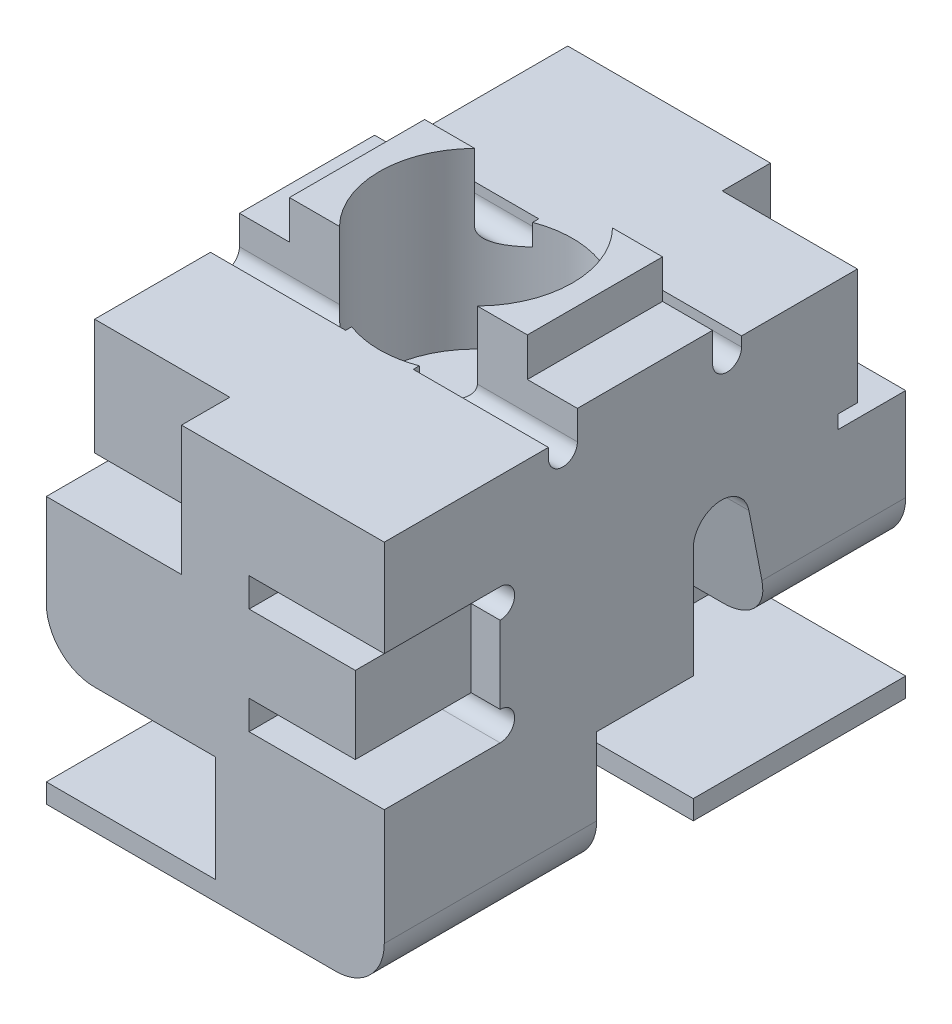
SolidWorks part; units mm, degrees
material "Brass"
ref_plane "Front Plane" through (0, 0, 0) normal (0, 0, 1) x (1, 0, 0)
ref_plane "Top Plane" through (0, 0, 0) normal (0, 1, 0) x (1, 0, 0)
ref_plane "Right Plane" through (0, 0, 0) normal (1, 0, 0) x (0, 0, -1)
sketch "Sketch1" plane through (0, 0, 0) normal (0, 1, 0) x (1, 0, 0)
  line L1 (0, 0) -> (4.445, 0)
  line L2 (0, 0) -> (0, 6.858)
  line L3 (0, 6.858) -> (4.445, 6.858)
  line L4 (4.445, 0) -> (4.445, 6.858)
  dimension "D1" = 4.445
  dimension "D2" = 6.858
extrude "Boss-Extrude1" add sketch "Sketch1" along normal blind 5.461
sketch "Sketch2" plane through (0, 5.461, 0) normal (0, 1, 0) x (1, 0, 0)
  line L0 (2.2225, 0) -> (2.2225, 6.858) construction
  line L1 (0, 0) -> (4.445, 0) construction
  line L2 (4.445, 6.858) -> (0, 6.858) construction
  circle A0 centre (2.2225, 3.429) radius 1.27
  dimension "D1" = 2.54
extrude "Cut-Extrude1" cut sketch "Sketch2" against normal blind 1.778
sketch "Sketch3" plane through (0, 0, 0) normal (-1, 0, 0) x (0, 0, 1)
  line L0 (-4.064, -1.651) -> (-4.064, 1.651)
  line L1 (-4.064, -1.651) -> (-2.794, -1.651)
  line L2 (-4.064, 1.651) -> (-2.794, 1.651)
  line L3 (-2.794, -1.651) -> (-2.794, 1.651)
  line L4 (-4.064, -1.651) -> (-2.794, 1.651) construction
  line L5 (-4.064, 1.651) -> (-2.794, -1.651) construction
  line L6 (-6.858, 0) -> (0, 0) construction
  point P1 (-3.429, 0)
  dimension "D1" = 1.27
  dimension "D2" = 3.302
extrude "Cut-Extrude2" cut sketch "Sketch3" against normal through all
sketch "Sketch4" plane through (0, 0, 0) normal (-1, 0, 0) x (0, 0, 1)
  line L0 (-2.794, 1.651) -> (-2.794, 3.1131)
  line L1 (-2.0619, 3.1692) -> (-1.7677, 1.651)
  line L2 (-1.7677, 1.651) -> (0, 1.651)
  line L3 (0, 5.461) -> (0, 0) construction
  line L4 (-2.794, 1.651) -> (-2.794, 0.254)
  line L5 (-2.794, 0.254) -> (0, 0.254)
  line L6 (0, 0.254) -> (0, 1.651)
  line L7 (-2.794, 0) -> (0, 0) construction
  arc A0 (-2.0619, 3.1692) -> (-2.794, 3.1131) centre (-2.4247, 3.0989) ccw
  dimension "D1" = 0.254
extrude "Cut-Extrude3" cut sketch "Sketch4" against normal offset from surface (2.2225 mm away) 2.2225 up to face at (4.445, 1.778, -3.429)
sketch "Sketch11" plane through (4.445, 0, 0) normal (1, 0, 0) x (0, 0, -1)
  line L2 (0, 1.651) -> (1.7677, 1.651) construction
  line L5 (2.794, 0.254) -> (2.794, 1.651) construction
  line L6 (6.858, 1.651) -> (6.858, 0.254)
  line L7 (4.064, 0.254) -> (6.858, 0.254)
  line L8 (4.064, 0) -> (6.858, 0) construction
  line L9 (0, 5.461) -> (0, -0.0004)
  line L10 (0, 5.461) -> (6.858, 5.461) construction
  line L12 (3.429, 5.461) -> (3.429, 1.651) construction
  line L13 (4.064, 0.254) -> (4.064, 1.651)
  line L15 (6.858, 1.651) -> (5.0903, 1.651)
  line L16 (5.0903, 1.651) -> (4.7961, 3.1692)
  line L17 (4.064, 3.1131) -> (4.064, 1.651)
  arc A0 (2.794, 3.1131) -> (2.0619, 3.1692) centre (2.4247, 3.0989) ccw construction
  arc A2 (4.064, 3.1131) -> (4.7961, 3.1692) centre (4.4333, 3.0989) cw
  line M9 (4.064, 1.651) -> (4.064, 0)
  line M11 (6.858, 0) -> (6.858, 5.461)
  dimension "D1" = 0.254
extrude "Cut-Extrude4" cut sketch "Sketch11" against normal up to surface (2.2225 mm away) contours A2 L17 L7 L15 L16 M9 M11 up to face at (2.2225, 1.7242, -1.7481)
sketch "Sketch12" plane through (4.445, 0, 0) normal (1, 0, 0) x (0, 0, -1)
  line L0 (0, 5.461) -> (0, 0) construction
  line L1 (0, 2.159) -> (1.524, 2.159)
  line L2 (0, 2.159) -> (0, 2.54)
  line L3 (0, 2.54) -> (1.524, 2.54)
  line L4 (2.794, 1.651) -> (4.064, 1.651) construction
  line L5 (0, 5.461) -> (6.858, 5.461) construction
  line L6 (0, 3.937) -> (1.524, 3.937)
  line L7 (0, 3.937) -> (0, 3.556)
  line L8 (0, 3.556) -> (1.524, 3.556)
  line L9 (2.54, 5.207) -> (2.54, 5.08)
  line L10 (0, 5.461) -> (2.54, 5.461)
  line L11 (0, 5.461) -> (0, 5.207)
  line L12 (0, 5.207) -> (2.159, 5.207)
  line L13 (2.54, 5.461) -> (2.54, 5.207)
  line L15 (4.699, 5.207) -> (4.318, 5.207) construction
  line L16 (4.699, 5.08) -> (4.699, 5.207)
  line L17 (6.858, 5.461) -> (6.858, 3.5052)
  line L18 (6.858, 5.461) -> (6.858, 1.651) construction
  line L19 (2.159, 5.08) -> (2.159, 5.207)
  line L20 (2.159, 5.207) -> (2.54, 5.207) construction
  line L21 (3.429, 5.461) -> (3.429, 1.651) construction
  line L22 (4.318, 5.461) -> (4.318, 5.207)
  line L23 (6.223, 5.207) -> (4.699, 5.207)
  line L25 (6.858, 5.461) -> (4.318, 5.461)
  line L26 (4.318, 5.207) -> (4.318, 5.08)
  line L27 (6.223, 5.207) -> (6.223, 3.683)
  line L28 (6.223, 3.683) -> (5.969, 3.683)
  line L29 (5.969, 3.683) -> (5.969, 3.5052)
  line L30 (5.969, 3.5052) -> (6.858, 3.5052)
  arc A0 (1.524, 3.937) -> (1.524, 3.556) centre (1.524, 3.7465) cw
  arc A1 (1.524, 2.54) -> (1.524, 2.159) centre (1.524, 2.3495) cw
  arc A2 (2.54, 5.08) -> (2.159, 5.08) centre (2.3495, 5.08) cw
  arc A3 (4.318, 5.08) -> (4.699, 5.08) centre (4.5085, 5.08) ccw
  dimension "D1" = 0.508
  dimension "D2" = 1.524
  dimension "D3" = 1.016
  dimension "D4" = 0.381
  dimension "D5" = 0.889
  dimension "D6" = 0.254
  dimension "D7" = 0.127
  dimension "D8" = 0.889
  dimension "D9" = 0.1778
  dimension "D10" = 0.635
  dimension "D11" = 1.524
extrude "Cut-Extrude6" cut sketch "Sketch12" against normal blind 1.778
sketch "Sketch13" plane through (0, 0, 0) normal (-1, 0, 0) x (0, 0, 1)
  line L0 (-6.858, 2.159) -> (-5.334, 2.159)
  line L1 (-6.858, 2.159) -> (-6.858, 2.54)
  line L2 (-6.858, 2.54) -> (-5.334, 2.54)
  line L3 (-6.858, 3.937) -> (-5.334, 3.937)
  line L4 (-6.858, 3.937) -> (-6.858, 3.556)
  line L5 (-6.858, 3.556) -> (-5.334, 3.556)
  line L6 (-4.318, 5.207) -> (-4.318, 5.08)
  line L7 (-6.858, 5.461) -> (-4.318, 5.461)
  line L8 (-6.858, 5.461) -> (-6.858, 5.207)
  line L9 (-6.858, 5.207) -> (-4.699, 5.207)
  line L10 (-4.318, 5.461) -> (-4.318, 5.207)
  line L11 (-2.159, 5.207) -> (-2.54, 5.207) construction
  line L12 (-2.159, 5.08) -> (-2.159, 5.207)
  line L13 (0, 5.461) -> (0, 3.5052)
  line L14 (-4.699, 5.08) -> (-4.699, 5.207)
  line L15 (-4.699, 5.207) -> (-4.318, 5.207) construction
  line L16 (-3.429, 5.461) -> (-3.429, 3.1024) construction
  line L17 (-2.54, 5.461) -> (-2.54, 5.207)
  line L18 (-0.635, 5.207) -> (-2.159, 5.207)
  line L19 (0, 5.461) -> (-2.54, 5.461)
  line L20 (-2.54, 5.207) -> (-2.54, 5.08)
  line L21 (-0.635, 5.207) -> (-0.635, 3.683)
  line L22 (-0.635, 3.683) -> (-0.889, 3.683)
  line L23 (-0.889, 3.683) -> (-0.889, 3.5052)
  line L24 (-0.889, 3.5052) -> (0, 3.5052)
  line L25 (-6.858, 5.461) -> (-6.858, 0) construction
  line L26 (-6.858, 5.461) -> (0, 5.461) construction
  arc A0 (-5.334, 3.937) -> (-5.334, 3.556) centre (-5.334, 3.7465) cw
  arc A1 (-5.334, 2.54) -> (-5.334, 2.159) centre (-5.334, 2.3495) cw
  arc A2 (-4.318, 5.08) -> (-4.699, 5.08) centre (-4.5085, 5.08) cw
  arc A3 (-2.54, 5.08) -> (-2.159, 5.08) centre (-2.3495, 5.08) ccw
  dimension "D1" = 1.524
  dimension "D2" = 1.016
  dimension "D3" = 0.381
  dimension "D4" = 0.889
  dimension "D5" = 0.254
  dimension "D6" = 0.127
  dimension "D7" = 0.889
  dimension "D8" = 0.1778
  dimension "D9" = 0.635
  dimension "D10" = 1.524
  dimension "D11" = 1.27
  dimension "D12" = 2.54
extrude "Cut-Extrude7" cut sketch "Sketch13" against normal blind 1.778
fillet "Fillet1" radius 0.635 4 edges at (4.445, 0, -1.397) (0, 0, -5.461) (4.445, 1.651, -5.9741) (0, 1.651, -0.8839)
sketch "Sketch14" plane through (0, 0, -6.858) normal (0, 0, -1) x (-1, 0, 0)
  line L1 (-2.667, 5.461) -> (-1.778, 5.461)
  line L2 (-2.667, 5.461) -> (-2.667, 5.207)
  line L3 (-2.667, 5.207) -> (-1.778, 5.207)
  line L4 (-1.778, 5.461) -> (-1.778, 5.207)
extrude "Cut-Extrude8" cut sketch "Sketch14" against normal through all
sketch "Sketch15" plane through (0, 5.461, 0) normal (0, 1, 0) x (1, 0, 0)
  line L0 (3.1295, 4.318) -> (3.7872, 4.318)
  line L1 (3.1295, 4.318) -> (4.445, 4.318) construction
  line L2 (3.7872, 4.318) -> (3.7872, 2.54)
  line L3 (3.1295, 2.54) -> (4.445, 2.54) construction
  line L4 (3.7872, 2.54) -> (3.1295, 2.54)
  line L5 (1.3155, 4.318) -> (0.6578, 4.318)
  line L6 (1.3155, 4.318) -> (0, 4.318) construction
  line L7 (0.6578, 4.318) -> (0.6578, 2.54)
  line L8 (1.3155, 2.54) -> (0, 2.54) construction
  line L9 (0.6578, 2.54) -> (1.3155, 2.54)
  arc A0 (1.3155, 4.318) -> (1.3155, 2.54) centre (2.2225, 3.429) ccw construction
  arc A1 (3.1295, 2.54) -> (3.1295, 4.318) centre (2.2225, 3.429) ccw construction
  arc A2 (1.3155, 4.318) -> (1.3155, 2.54) centre (2.2225, 3.429) ccw
  arc A3 (3.1295, 2.54) -> (3.1295, 4.318) centre (2.2225, 3.429) ccw
extrude "Boss-Extrude2" add sketch "Sketch15" along normal blind 0.508
sketch "Sketch16" plane through (0, 0, 0) normal (-1, 0, 0) x (0, 0, 1)
  line L1 (-6.858, 3.556) -> (-5.334, 3.556)
  line L2 (-6.858, 3.556) -> (-6.858, 2.54)
  line L3 (-6.858, 2.54) -> (-5.334, 2.54)
  line L4 (-5.334, 3.556) -> (-5.334, 2.54)
extrude "Cut-Extrude9" cut sketch "Sketch16" against normal blind 0.381
sketch "Sketch17" plane through (4.445, 0, 0) normal (1, 0, 0) x (0, 0, -1)
  line L1 (0, 2.54) -> (1.524, 2.54)
  line L2 (0, 2.54) -> (0, 3.556)
  line L3 (0, 3.556) -> (1.524, 3.556)
  line L4 (1.524, 2.54) -> (1.524, 3.556)
extrude "Cut-Extrude10" cut sketch "Sketch17" against normal blind 0.381
